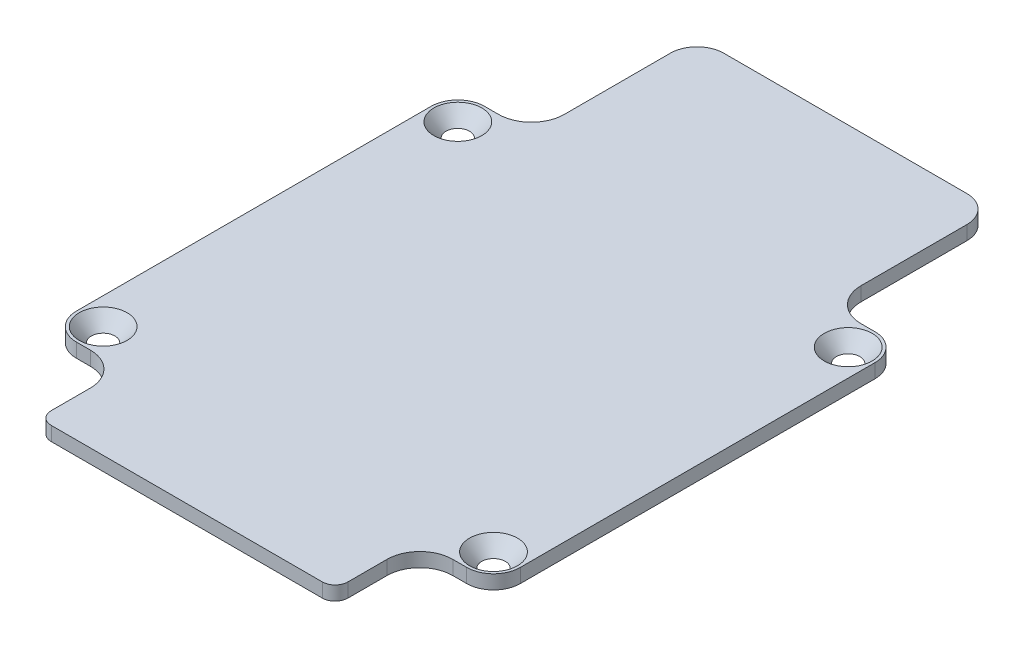
SolidWorks part; units mm, degrees
ref_plane "Front Plane" through (0, 0, 0) normal (0, 0, 1) x (1, 0, 0)
ref_plane "Top Plane" through (0, 0, 0) normal (0, 1, 0) x (1, 0, 0)
ref_plane "Right Plane" through (0, 0, 0) normal (1, 0, 0) x (0, 0, -1)
sketch "Sketch1" plane through (0, 9.525, 0) normal (0, 1, 0) x (1, 0, 0)
  line L24 (-16.891, 39.0525) -> (-16.891, 26.9875)
  line L25 (-20.6375, 23.241) -> (-22.225, 23.241)
  line L26 (-25.273, 20.193) -> (-25.273, -20.193)
  line L27 (-22.225, -23.241) -> (-20.6375, -23.241)
  line L28 (-16.891, -26.9875) -> (-16.891, -31.4325)
  line L29 (-15.4305, -32.893) -> (15.4305, -32.893)
  line L40 (16.891, -31.4325) -> (16.891, -26.9875)
  line L42 (20.6375, -23.241) -> (22.225, -23.241)
  line L43 (25.273, -20.193) -> (25.273, 20.193)
  line L44 (22.225, 23.241) -> (20.6375, 23.241)
  line L45 (16.891, 26.9875) -> (16.891, 39.0525)
  line L58 (13.843, 42.1005) -> (-13.843, 42.1005)
  line L59 (-16.891, 39.0525) -> (-16.891, 26.9875)
  line L60 (-20.6375, 23.241) -> (-22.225, 23.241)
  line L61 (-25.273, 20.193) -> (-25.273, -20.193)
  line L62 (-22.225, -23.241) -> (-20.6375, -23.241)
  line L63 (-16.891, -26.9875) -> (-16.891, -31.4325)
  line L64 (-15.4305, -32.893) -> (15.4305, -32.893)
  line L65 (16.891, -31.4325) -> (16.891, -26.9875)
  line L66 (20.6375, -23.241) -> (22.225, -23.241)
  line L67 (25.273, -20.193) -> (25.273, 20.193)
  line L68 (22.225, 23.241) -> (20.6375, 23.241)
  line L69 (16.891, 26.9875) -> (16.891, 39.0525)
  line L70 (13.843, 42.1005) -> (-13.843, 42.1005)
  arc A24 (-20.6375, 23.241) -> (-16.891, 26.9875) centre (-20.6375, 26.9875) ccw
  arc A25 (-22.225, 23.241) -> (-25.273, 20.193) centre (-22.225, 20.193) ccw
  arc A26 (-25.273, -20.193) -> (-22.225, -23.241) centre (-22.225, -20.193) ccw
  arc A27 (-16.891, -26.9875) -> (-20.6375, -23.241) centre (-20.6375, -26.9875) ccw
  arc A28 (-16.891, -31.4325) -> (-15.4305, -32.893) centre (-15.4305, -31.4325) ccw
  arc A29 (15.4305, -32.893) -> (16.891, -31.4325) centre (15.4305, -31.4325) ccw
  arc A31 (20.6375, -23.241) -> (16.891, -26.9875) centre (20.6375, -26.9875) ccw
  arc A33 (22.225, -23.241) -> (25.273, -20.193) centre (22.225, -20.193) ccw
  arc A34 (25.273, 20.193) -> (22.225, 23.241) centre (22.225, 20.193) ccw
  arc A35 (16.891, 26.9875) -> (20.6375, 23.241) centre (20.6375, 26.9875) ccw
  arc A60 (16.891, 39.0525) -> (13.843, 42.1005) centre (13.843, 39.0525) ccw
  arc A61 (-13.843, 42.1005) -> (-16.891, 39.0525) centre (-13.843, 39.0525) ccw
  arc A62 (-20.6375, 23.241) -> (-16.891, 26.9875) centre (-20.6375, 26.9875) ccw
  arc A63 (-22.225, 23.241) -> (-25.273, 20.193) centre (-22.225, 20.193) ccw
  arc A64 (-25.273, -20.193) -> (-22.225, -23.241) centre (-22.225, -20.193) ccw
  arc A65 (-16.891, -26.9875) -> (-20.6375, -23.241) centre (-20.6375, -26.9875) ccw
  arc A66 (-16.891, -31.4325) -> (-15.4305, -32.893) centre (-15.4305, -31.4325) ccw
  arc A67 (15.4305, -32.893) -> (16.891, -31.4325) centre (15.4305, -31.4325) ccw
  arc A68 (20.6375, -23.241) -> (16.891, -26.9875) centre (20.6375, -26.9875) ccw
  arc A69 (22.225, -23.241) -> (25.273, -20.193) centre (22.225, -20.193) ccw
  arc A70 (25.273, 20.193) -> (22.225, 23.241) centre (22.225, 20.193) ccw
  arc A71 (16.891, 26.9875) -> (20.6375, 23.241) centre (20.6375, 26.9875) ccw
  arc A72 (16.891, 39.0525) -> (13.843, 42.1005) centre (13.843, 39.0525) ccw
  arc A73 (-13.843, 42.1005) -> (-16.891, 39.0525) centre (-13.843, 39.0525) ccw
  dimension "D1" = 0.127
extrude "Boss-Extrude3" add sketch "Sketch1" against normal blind 1.6
sketch "Sketch4" plane through (0, 9.525, 0) normal (0, -1, 0) x (-1, 0, 0)
  point P0 (-22.225, -20.193)
  point P1 (22.225, -20.193)
  point P3 (22.225, 20.193)
  point P5 (-22.225, 20.193)
hole_wizard "CSK for #2 Flat Head Machine Screw1" positions "3DSketch2" profile "Sketch5" countersink size "#2" standard "ANSI Inch"
sketch3d "3DSketch2"
  point P0 (22.225, 9.525, 20.193)
  point P3 (-22.225, 9.525, 20.193)
  point P6 (-22.225, 9.525, -20.193)
  point P9 (22.225, 9.525, -20.193)
sketch "Sketch5" plane through (22.225, 9.525, 20.193) normal (1, 0, 0) x (0, 0, 1)
  line L0 (0, 0) -> (0, 6.3206)
  line L1 (0, 6.3206) -> (1.2192, 5.588)
  line L2 (1.2192, 5.588) -> (1.2192, 1.7386)
  line L3 (1.2192, 1.7386) -> (2.7305, 0)
  line L5 (2.7305, 0) -> (0, 0)
  line L6 (-1.2192, 1.7386) -> (-2.7305, 0) construction
  line L10 (0, 6.3206) -> (-1.2192, 5.588) construction
  line L11 (0, -6.35) -> (0, 107.95) construction
  dimension "Hole Dia." = 2.4384
  dimension "Hole Depth" = 5.588
  dimension "Near C'Sink Dia." = 5.461
  dimension "Near C'Sink Angle" = 82
  dimension "Drill Angle" = 118
